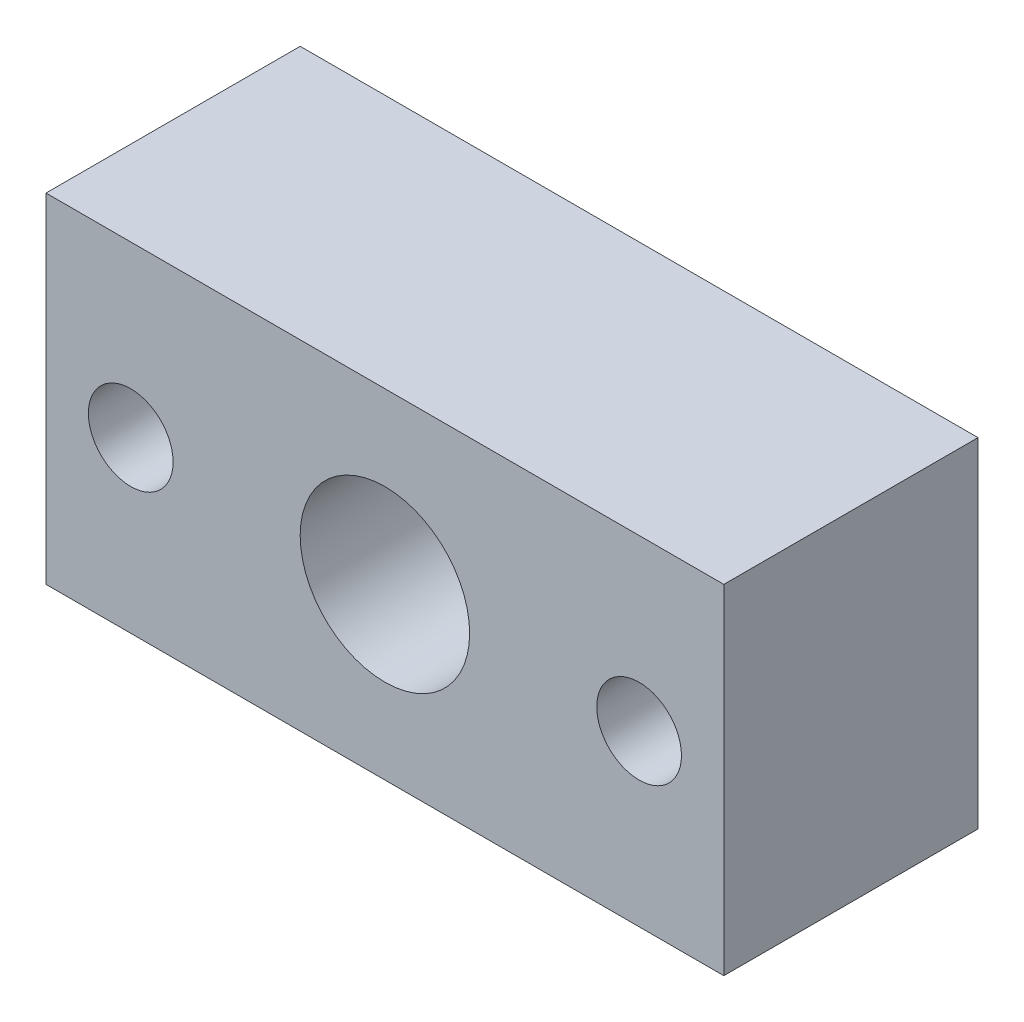
SolidWorks part; units mm, degrees
ref_plane "Front Plane" through (0, 0, 0) normal (0, 0, 1) x (1, 0, 0)
ref_plane "Top Plane" through (0, 0, 0) normal (0, 1, 0) x (1, 0, 0)
ref_plane "Right Plane" through (0, 0, 0) normal (1, 0, 0) x (0, 0, -1)
sketch "Sketch1" plane through (0, 0, 0) normal (0, 0, 1) x (1, 0, 0)
  line L1 (0, 0) -> (40, 0)
  line L2 (0, 0) -> (0, 20)
  line L3 (0, 20) -> (40, 20)
  line L4 (40, 0) -> (40, 20)
  circle A0 centre (20, 10) radius 5
  circle A1 centre (35, 10) radius 2.5
  circle A2 centre (5, 10) radius 2.5
  point P11 (178.8347, 10)
  point P12 (0, 0)
  point P13 (191.6205, 10)
  point P14 (167.632, 10)
  point P15 (0, 0)
  point P16 (0, 0)
  point P23 (0, 0)
  dimension "D1" = 40
  dimension "D2" = 20
extrude "Boss-Extrude1" add sketch "Sketch1" along normal blind 15
